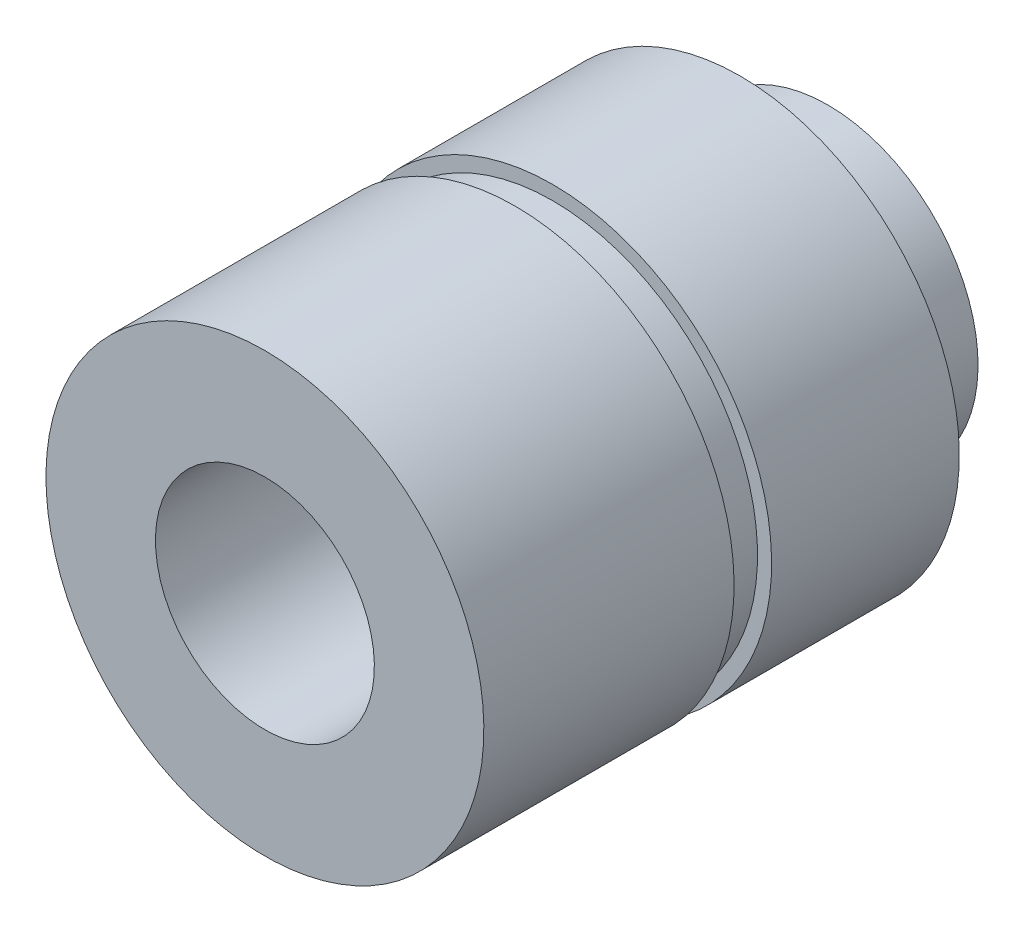
SolidWorks part; units mm, degrees
ref_plane "Front Plane" through (0, 0, 0) normal (0, 0, 1) x (1, 0, 0)
ref_plane "Top Plane" through (0, 0, 0) normal (0, 1, 0) x (1, 0, 0)
ref_plane "Right Plane" through (0, 0, 0) normal (1, 0, 0) x (0, 0, -1)
sketch "Sketch1" plane through (0, 0, 0) normal (1, 0, 0) x (0, 0, -1)
  line L0 (0, 7) -> (8, 7)
  line L1 (8, 7) -> (8, 6.55)
  line L2 (8, 6.55) -> (9.2, 6.55)
  line L3 (9.2, 6.55) -> (9.2, 7)
  line L4 (9.2, 7) -> (15.2, 7)
  line L5 (15.2, 7) -> (15.2, 4.8)
  line L6 (15.2, 4.8) -> (18, 4.8)
  line L7 (18, 4.8) -> (18, 3.5)
  line L8 (18, 0) -> (0, 0) construction
  line L9 (0, 3.5) -> (0, 7)
  line L10 (0, 3.5) -> (18, 3.5)
  point P13 (0, 0)
  dimension "D1" = 6.55
  dimension "D2" = 1.2
  dimension "D3" = 18
  dimension "D4" = 10
  dimension "D5" = 7
  dimension "D6" = 3.5
  dimension "D7" = 6
  dimension "D8" = 4.8
revolve "Revolve1" add sketch "Sketch1" angle 360 about L8
